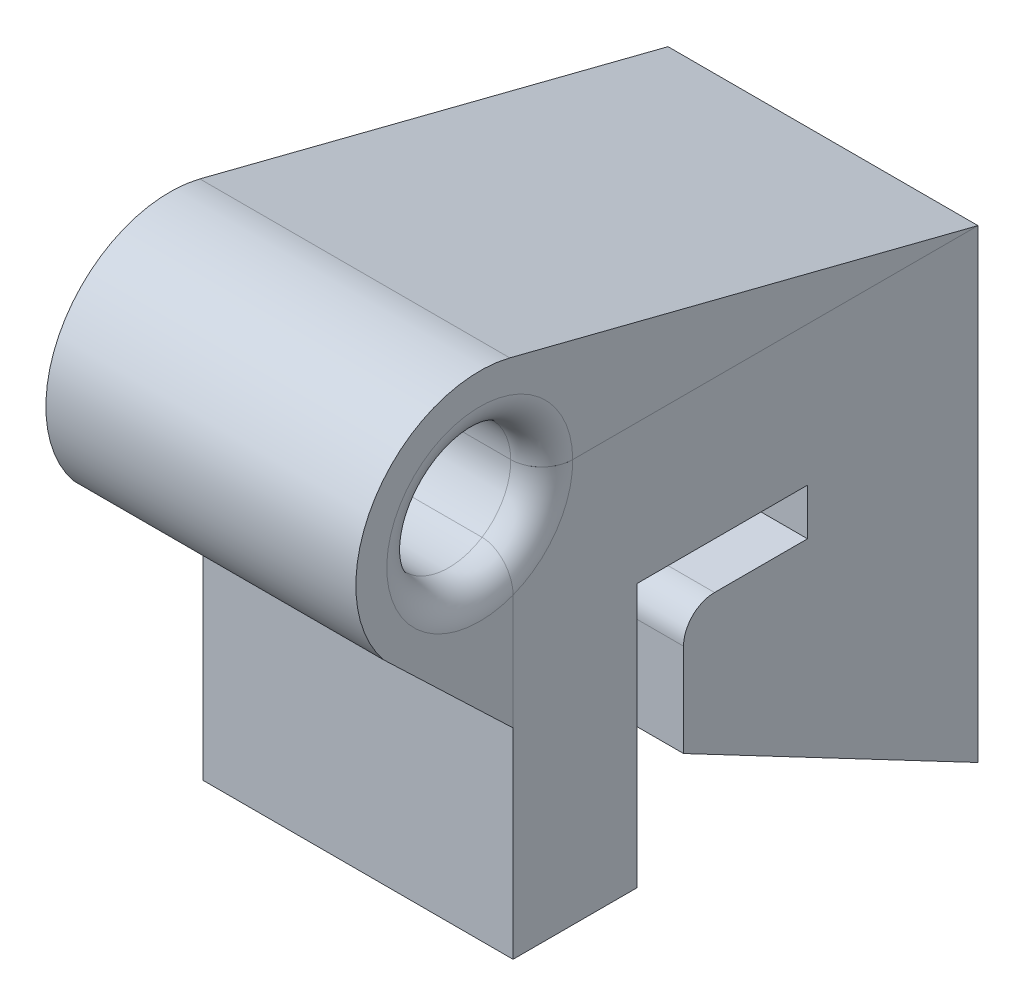
SolidWorks part; units mm, degrees
ref_plane "Front Plane" through (0, 0, 0) normal (0, 0, 1) x (1, 0, 0)
ref_plane "Top Plane" through (0, 0, 0) normal (0, 1, 0) x (1, 0, 0)
ref_plane "Right Plane" through (0, 0, 0) normal (1, 0, 0) x (0, 0, -1)
sketch "Esquisse5" plane through (0, 0, 0) normal (1, 0, 0) x (0, 0, -1)
  line L0 (0, -5) -> (0, 10)
  line L1 (0, 10) -> (-15, 10)
  line L2 (-15, 10) -> (-15, -3)
  line L3 (-15, -3) -> (-11, -3)
  line L4 (-11, -3) -> (-11, 5.5)
  line L5 (-11, 5.5) -> (-5.5, 5.5)
  line L6 (-5.5, 5.5) -> (-5.5, 4)
  line L7 (-5.5, 4) -> (-9.5, 4)
  line L8 (-9.5, 4) -> (-9.5, 0)
  line L9 (-9.5, 0) -> (0, -5)
  point P2 (0, 0)
  point P5 (0, 0)
  point P12 (0, 0)
  point P13 (0, 0)
  point P14 (0, 0)
  point P15 (0, 0)
  point P16 (0, 0)
  point P17 (0, 0)
  point P18 (0, 0)
  point P19 (0, 0)
  point P20 (0, -5)
  dimension "D1" = 4
  dimension "D2" = 1.5
  dimension "D3" = 4
  dimension "D4" = 4
  dimension "D5" = 1.5
  dimension "D6" = 62.241
  dimension "D7" = 15
  dimension "D8" = 15
extrude "Boss.-Extru.5" add sketch "Esquisse5" along normal blind 10
fillet "Congé1" radius 1 1 edges at (5, 4, 9.5)
sketch "Esquisse7" plane through (0, 0, 0) normal (-1, 0, 0) x (0, 0, 1)
  line L0 (0, 10) -> (15.1044, 13.8572)
  line L1 (19.1697, 7.4495) -> (15, 3.4666)
  line L2 (15, 10) -> (15, -3) construction
  line L3 (15, 3.4666) -> (15, 10)
  line L4 (15, 10) -> (0, 10)
  arc A0 (19.1697, 7.4495) -> (15.1044, 13.8572) centre (16.074, 9.9789) ccw
extrude "Boss.-Extru.6" add sketch "Esquisse7" against normal blind 10 separate body
sketch "Esquisse8" plane through (10, 0, 0) normal (1, 0, 0) x (0, 0, -1)
  line L0 (-15.1044, 13.8572) -> (-16.074, 9.9789) construction
  line L1 (-16.074, 9.9789) -> (-19.1697, 7.4495) construction
  line L2 (-16.074, 9.9789) -> (-12.6984, 7.8373) construction
  circle A0 centre (-16.074, 9.9789) radius 2
  arc A1 (-15.1044, 13.8572) -> (-19.1697, 7.4495) centre (-16.074, 9.9789) ccw construction
  point P2 (15.3462, 9.5171)
  point P5 (0, 0)
  point P12 (-12.6984, 7.8373)
extrude "Enlèv. mat.-Extru.1" cut sketch "Esquisse8" against normal through all
fillet "Congé3" radius 1 1 edges at (0, 10.9319, 17.8323)
fillet "Congé4" radius 1 1 edges at (10, 10.9319, 17.8323)
fillet "Congé5" radius 1 1 edges at (10, 9.0259, 14.3157)
fillet "Congé6" radius 1 1 edges at (0, 9.0259, 14.3157)
